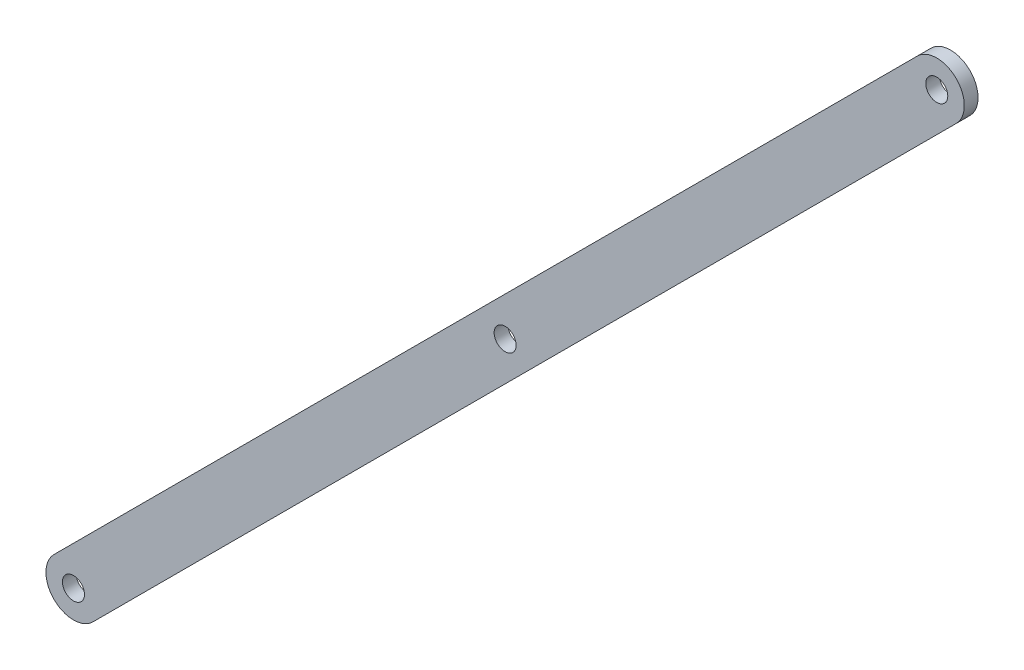
SolidWorks part; units mm, degrees
ref_plane "Alzado" through (0, 0, 0) normal (0, 0, 1) x (1, 0, 0)
ref_plane "Planta" through (0, 0, 0) normal (0, 1, 0) x (1, 0, 0)
ref_plane "Vista lateral" through (0, 0, 0) normal (1, 0, 0) x (0, 0, -1)
sketch "Croquis1" plane through (0, 0, 0) normal (0, 0, 1) x (1, 0, 0)
  line L0 (0, 0) -> (131.9173, 0) construction
  line L1 (0, 0) -> (313.6726, 313.6726) construction
  line L2 (0, 0) -> (313.6726, 313.6726) construction
  line L3 (-7.0711, 7.0711) -> (306.6015, 320.7436)
  line L4 (7.0711, -7.0711) -> (320.7436, 306.6015)
  line L5 (175.3013, 196.0206) -> (178.0259, 152.7087) construction
  arc A0 (-7.0711, 7.0711) -> (7.0711, -7.0711) centre (0, 0) ccw
  arc A1 (320.7436, 306.6015) -> (306.6015, 320.7436) centre (313.6726, 313.6726) ccw
  circle A3 centre (313.6726, 313.6726) radius 4
  circle A5 centre (0, 0) radius 4
  circle A6 centre (156.8363, 156.8363) radius 4
  point P3 (156.8363, 156.8363)
  dimension "D4" = 8
  dimension "D5" = 8
  dimension "D6" = 8
  dimension "D1" = 45
  dimension "D2" = 443.6
  dimension "D3" = 20
extrude "Saliente-Extruir1" add sketch "Croquis1" along normal blind 5
